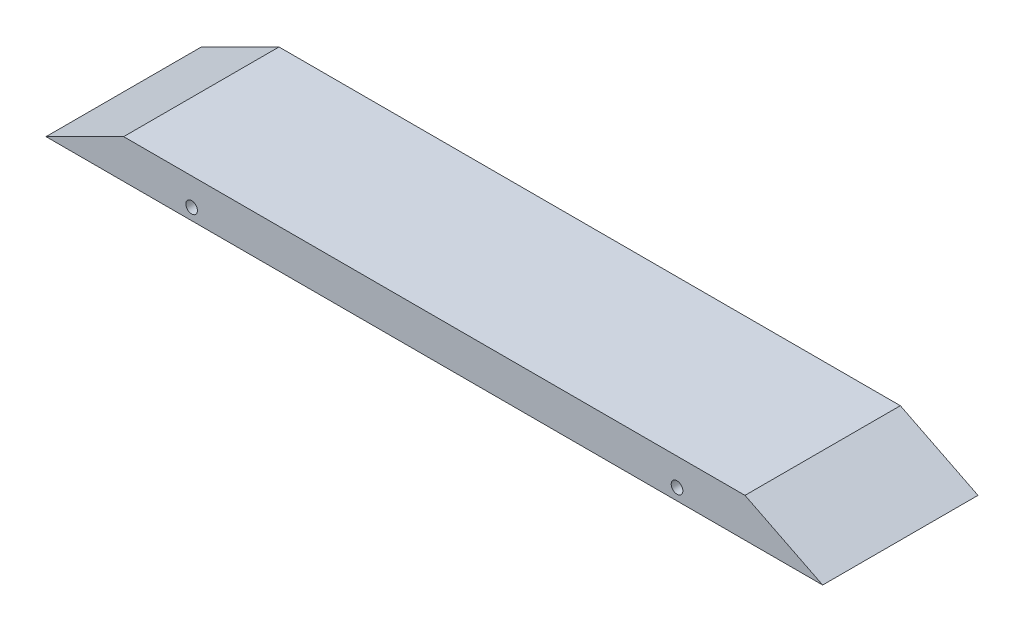
SolidWorks part; units mm, degrees
ref_plane "前视基准面" through (0, 0, 0) normal (0, 0, 1) x (1, 0, 0)
ref_plane "上视基准面" through (0, 0, 0) normal (0, 1, 0) x (1, 0, 0)
ref_plane "右视基准面" through (0, 0, 0) normal (1, 0, 0) x (0, 0, -1)
other "Configuration Table"
sketch "草图1" plane through (0, 0, 0) normal (0, 0, 1) x (1, 0, 0)
  line L0 (0, 0) -> (200, 0)
  line L1 (200, 0) -> (180, 10)
  line L2 (180, 10) -> (20, 10)
  line L3 (20, 10) -> (0, 0)
  point P3 (0, 0)
  dimension "D1" = 200
  dimension "D2" = 160
  dimension "D3" = 10
  dimension "D4" = 20
extrude "凸台-拉伸1" add sketch "草图1" along normal blind 40
sketch "草图2" plane through (0, 0, 40) normal (0, 0, 1) x (1, 0, 0)
  line L0 (0, 0) -> (200, 0) construction
  line L1 (100, 43.8143) -> (100, -26.9852) construction
  circle A0 centre (37.5, 3) radius 1.5
  circle A1 centre (162.5, 3) radius 1.5
  point P6 (0, 0)
  point P9 (0, 0)
  dimension "D2" = 3
  dimension "D3" = 3
  dimension "D1" = 125
  dimension "D5" = 3
extrude "切除-拉伸1" cut sketch "草图2" against normal through all
